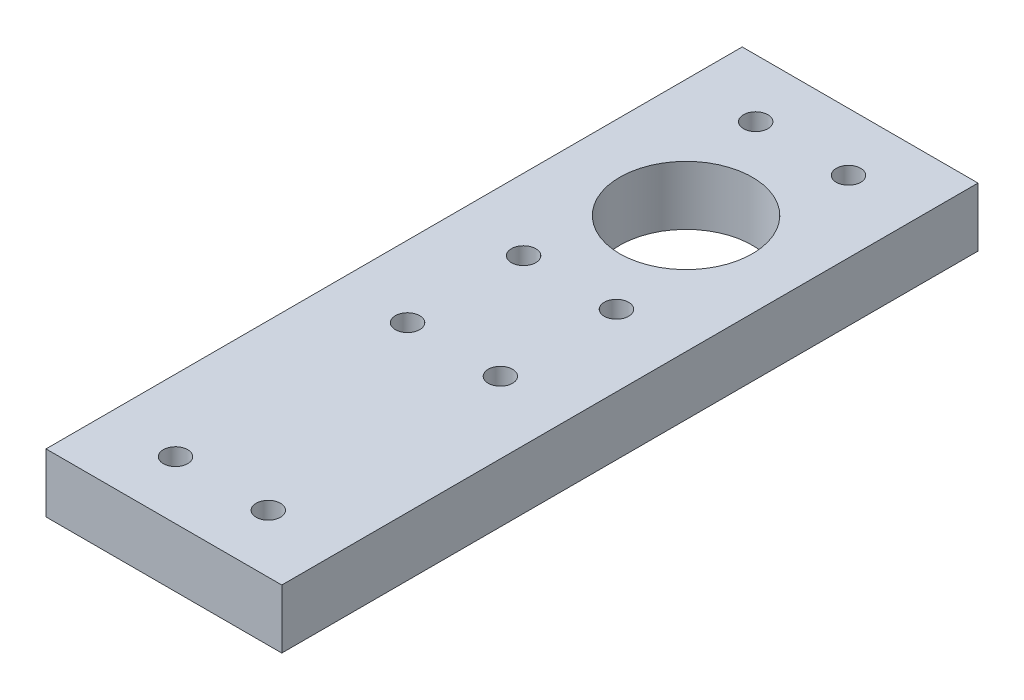
SolidWorks part; units mm, degrees
ref_plane "Front Plane" through (0, 0, 0) normal (0, 0, 1) x (1, 0, 0)
ref_plane "Top Plane" through (0, 0, 0) normal (0, 1, 0) x (1, 0, 0)
ref_plane "Right Plane" through (0, 0, 0) normal (1, 0, 0) x (0, 0, -1)
sketch "Sketch2" plane through (0, 0, 0) normal (0, 1, 0) x (1, 0, 0)
  line L1 (0, 0) -> (101.6, 0)
  line L2 (0, 0) -> (0, 300)
  line L3 (0, 300) -> (101.6, 300)
  line L4 (101.6, 0) -> (101.6, 300)
  dimension "D1" = 101.6
  dimension "D2" = 300
extrude "Boss-Extrude1" add sketch "Sketch2" along normal blind 25.4
sketch "Sketch3" plane through (0, 25.4, 0) normal (0, 1, 0) x (1, 0, 0)
  line L1 (0, 300) -> (50.8, 300)
  line L2 (0, 300) -> (0, 225)
  line L3 (0, 225) -> (50.8, 225)
  line L4 (50.8, 300) -> (50.8, 225)
  line L5 (30.8, 275) -> (70.8, 275)
  line L6 (30.8, 275) -> (30.8, 175)
  line L7 (30.8, 175) -> (70.8, 175)
  line L8 (70.8, 275) -> (70.8, 175)
  line L9 (30.8, 275) -> (70.8, 175) construction
  line L10 (30.8, 175) -> (70.8, 275) construction
  circle A0 centre (70.8, 275) radius 5.25
  circle A1 centre (30.8, 275) radius 5.25
  circle A2 centre (70.8, 175) radius 5.25
  circle A3 centre (30.8, 175) radius 5.25
  circle A4 centre (50.8, 225) radius 28.575
  dimension "D1" = 50.8
  dimension "D2" = 75
  dimension "D3" = 40
  dimension "D4" = 100
extrude "Cut-Extrude1" cut sketch "Sketch3" against normal blind 25.4 contours A1 | A0 | A4 | A2 | A3
sketch "Sketch4" plane through (0, 25.4, 0) normal (0, 1, 0) x (1, 0, 0)
  line L1 (0, 300) -> (50.8, 300)
  line L2 (0, 300) -> (0, 75)
  line L3 (0, 75) -> (50.8, 75)
  line L4 (50.8, 300) -> (50.8, 75)
  line L5 (30.8, 25) -> (70.8, 25)
  line L6 (30.8, 25) -> (30.8, 125)
  line L7 (30.8, 125) -> (70.8, 125)
  line L8 (70.8, 25) -> (70.8, 125)
  line L9 (30.8, 25) -> (70.8, 125) construction
  line L10 (30.8, 125) -> (70.8, 25) construction
  circle A0 centre (70.8, 125) radius 5.25
  circle A1 centre (30.8, 125) radius 5.25
  circle A2 centre (30.8, 25) radius 5.25
  circle A3 centre (70.8, 25) radius 5.25
  dimension "D1" = 50.8
  dimension "D2" = 225
  dimension "D3" = 40
  dimension "D4" = 100
extrude "Cut-Extrude2" cut sketch "Sketch4" against normal blind 25.4 contours A1 | A0 | A3 | A2
